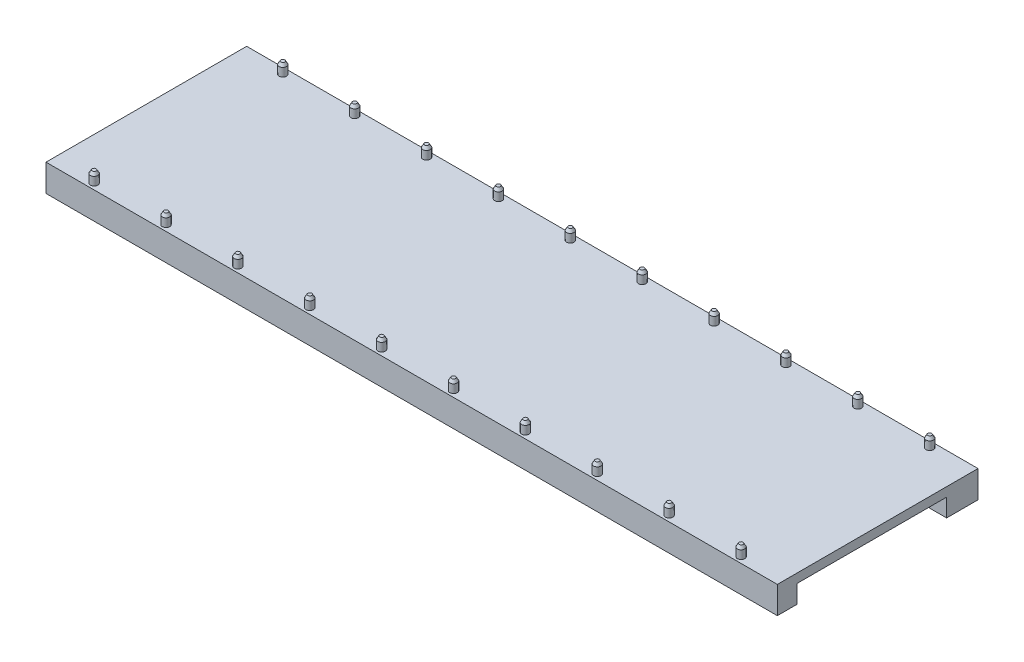
SolidWorks part; units mm, degrees
ref_plane "Front" through (0, 0, 0) normal (0, 0, 1) x (1, 0, 0)
ref_plane "Top" through (0, 0, 0) normal (0, 1, 0) x (1, 0, 0)
ref_plane "Right" through (0, 0, 0) normal (1, 0, 0) x (0, 0, -1)
sketch "Sketch1" plane through (0, 0, 0) normal (0, 1, 0) x (1, 0, 0)
  line L1 (0, 0) -> (488.315, 0)
  line L2 (0, 0) -> (0, -133.985)
  line L3 (0, -133.985) -> (488.315, -133.985)
  line L4 (488.315, 0) -> (488.315, -133.985)
  dimension "D1" = 488.315
  dimension "D2" = 133.985
extrude "Boss-Extrude1" add sketch "Sketch1" against normal blind 6.0452
sketch "Sketch2" plane through (0, 0, 0) normal (0, 1, 0) x (1, 0, 0)
  line L0 (0, 0) -> (0, -133.985) construction
  line L1 (28.1305, -4.0005) -> (28.1305, -129.9845) construction
  circle A0 centre (28.1305, -4.0005) radius 2.4765
  circle A1 centre (76.1365, -4.0005) radius 2.4765
  circle A2 centre (28.1305, -129.9845) radius 2.4765
  circle A3 centre (76.1365, -129.9845) radius 2.4765
  point P10 (0, -66.9925)
  point P11 (28.1305, -66.9925)
  dimension "D1" = 4.953
  dimension "D2" = 28.1305
  dimension "D3" = 48.006
  dimension "D4" = 125.984
extrude "Boss-Extrude2" add sketch "Sketch2" along normal blind 7.62
chamfer "Chamfer1" distance 2.032 angle 30 4 edges at (76.1365, 7.62, 132.461) (28.1305, 7.62, 132.461) (76.1365, 7.62, 6.477) (28.1305, 7.62, 6.477)
pattern_linear "LPattern1" count 5 spacing 95.9866 along (1, 0, 0) of "Boss-Extrude2", "Chamfer1"
sketch "Sketch3" plane through (0, 0, 0) normal (1, 0, 0) x (0, 0, -1)
  line L1 (0, -6.0452) -> (-20.955, -6.0452)
  line L2 (0, -6.0452) -> (0, -18.1102)
  line L3 (0, -18.1102) -> (-20.955, -18.1102)
  line L4 (-20.955, -6.0452) -> (-20.955, -18.1102)
  line L5 (-133.985, -6.0452) -> (-120.9802, -6.0452)
  line L6 (-133.985, -6.0452) -> (-133.985, -18.1102)
  line L7 (-133.985, -18.1102) -> (-120.9802, -18.1102)
  line L8 (-120.9802, -6.0452) -> (-120.9802, -18.1102)
  dimension "D1" = 20.955
  dimension "D2" = 13.0048
  dimension "D3" = 12.065
extrude "Boss-Extrude3" add sketch "Sketch3" along normal up to surface (488.315 mm away) up to face at (488.315, -3.0226, 66.9925)
